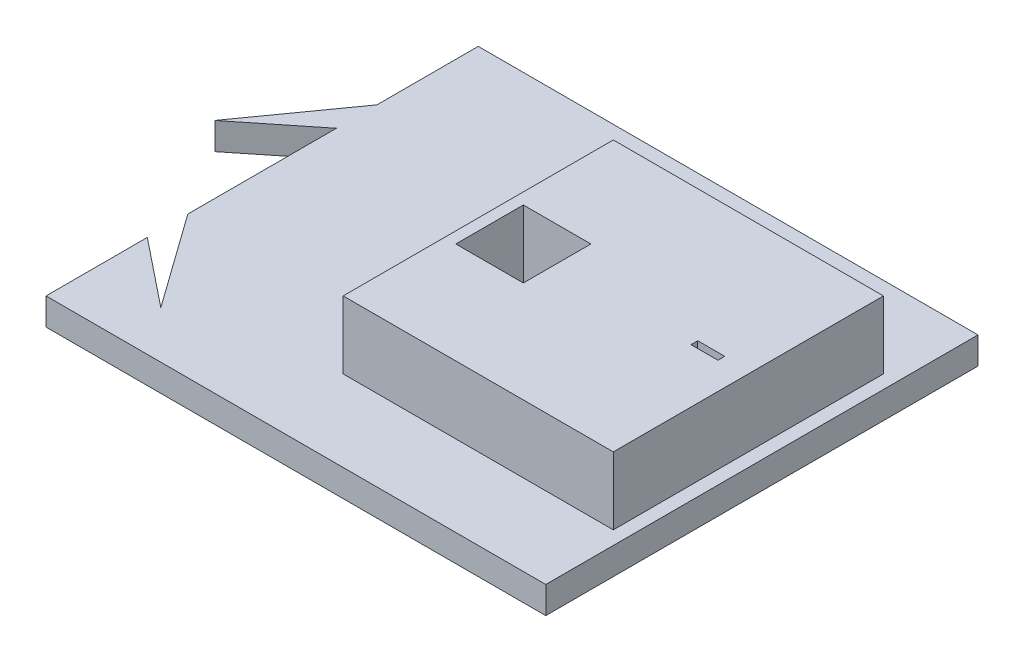
SolidWorks part; units mm, degrees
ref_plane "Front Plane" through (0, 0, 0) normal (0, 0, 1) x (1, 0, 0)
ref_plane "Top Plane" through (0, 0, 0) normal (0, 1, 0) x (1, 0, 0)
ref_plane "Right Plane" through (0, 0, 0) normal (1, 0, 0) x (0, 0, -1)
sketch "Sketch1" plane through (0, 0, 0) normal (0, 1, 0) x (1, 0, 0)
  line L0 (0, 75) -> (50, 35)
  line L1 (0, 0) -> (370, 0)
  line L2 (0, 0) -> (0, 75)
  line L3 (0, 320) -> (370, 320)
  line L4 (370, 0) -> (370, 320)
  line L5 (50, 35) -> (0, 105)
  line L6 (0, 215) -> (-50, 175)
  line L7 (-50, 175) -> (0, 245)
  line L8 (0, 245) -> (0, 320)
  line L9 (0, 105) -> (0, 215)
  dimension "D1" = 370
  dimension "D2" = 320
  dimension "D3" = 75
  dimension "D4" = 40
  dimension "D6" = 40
  dimension "D7" = 75
  dimension "D8" = 50
  dimension "D9" = 110
  dimension "D10" = 30
  dimension "D11" = 50
extrude "Boss-Extrude1" add sketch "Sketch1" along normal blind 20
sketch "Sketch2" plane through (0, 0, 0) normal (0, -1, 0) x (1, 0, 0)
  line L1 (340, -162.5) -> (320, -162.5)
  line L2 (340, -162.5) -> (340, -157.5)
  line L3 (340, -157.5) -> (320, -157.5)
  line L4 (320, -162.5) -> (320, -157.5)
  line L5 (370, 0) -> (370, -320) construction
  line L6 (0, 0) -> (370, 0) construction
  dimension "D1" = 30
  dimension "D2" = 157.5
  dimension "D3" = 5
  dimension "D4" = 20
extrude "Cut-Extrude1" cut sketch "Sketch2" against normal through all both and the other way through all
sketch "Sketch3" plane through (0, 20, 0) normal (0, 1, 0) x (1, 0, 0)
  line L9 (320, 157.5) -> (320, 162.5) construction
  line L26 (360, 60) -> (160, 60)
  line L27 (360, 60) -> (360, 260)
  line L28 (360, 260) -> (160, 260)
  line L29 (160, 60) -> (160, 260)
  line L30 (218.4, 135) -> (168.4, 135)
  line L31 (218.4, 135) -> (218.4, 185)
  line L32 (218.4, 185) -> (168.4, 185)
  line L33 (168.4, 135) -> (168.4, 185)
  line L34 (370, 320) -> (0, 320) construction
  line L35 (340, 162.5) -> (340, 157.5) construction
  point P5 (150.697, 150.2528)
  point P12 (193.4, 185)
  dimension "D1" = 101.6
  dimension "D2" = 75
  dimension "D3" = 60
  dimension "D4" = 200
  dimension "D5" = 20
  dimension "D6" = 50
extrude "Boss-Extrude2" add sketch "Sketch3" along normal blind 50
sketch "Sketch4" plane through (0, 0, 0) normal (0, -1, 0) x (1, 0, 0)
  line L1 (320, -157.5) -> (340, -157.5)
  line L2 (320, -157.5) -> (320, -162.5)
  line L3 (320, -162.5) -> (340, -162.5)
  line L4 (340, -157.5) -> (340, -162.5)
extrude "Cut-Extrude2" cut sketch "Sketch4" against normal through all
